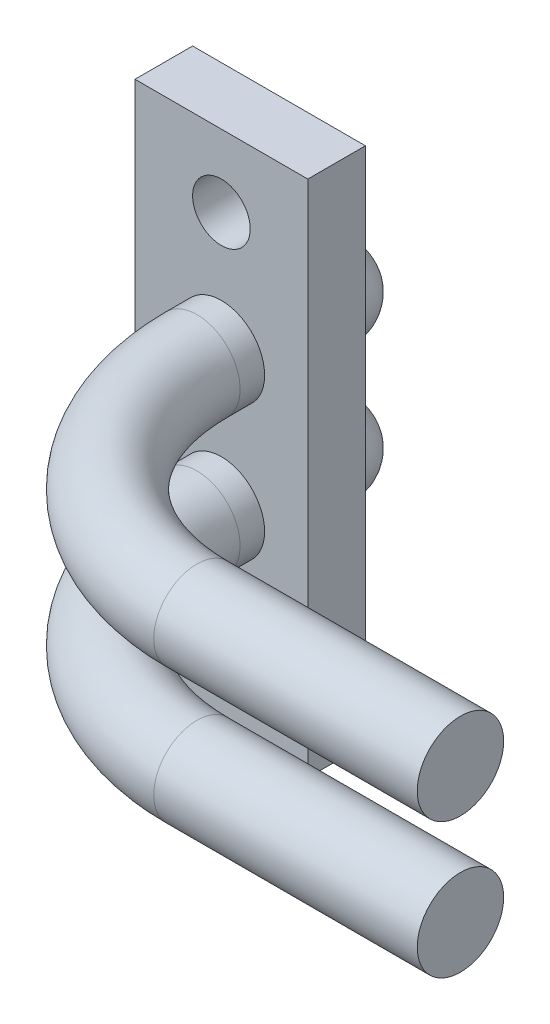
SolidWorks part; units mm, degrees
ref_plane "Front Plane" through (0, 0, 0) normal (0, 0, 1) x (1, 0, 0)
ref_plane "Top Plane" through (0, 0, 0) normal (0, 1, 0) x (1, 0, 0)
ref_plane "Right Plane" through (0, 0, 0) normal (1, 0, 0) x (0, 0, -1)
sketch "Sketch1" plane through (0, 0, 0) normal (0, 0, 1) x (1, 0, 0)
  line L1 (-3, -9) -> (3, -9)
  line L2 (-3, -9) -> (-3, 9)
  line L3 (-3, 9) -> (3, 9)
  line L4 (3, -9) -> (3, 9)
  line L5 (-3, -9) -> (3, 9) construction
  line L6 (-3, 9) -> (3, -9) construction
  point P0 (0, 0)
  dimension "D1" = 18
  dimension "D2" = 6
extrude "Boss-Extrude1" add sketch "Sketch1" along normal blind 2
sketch "Sketch2" plane through (0, 0, 0) normal (0, 0, -1) x (-1, 0, 0)
  circle A0 centre (0, 2.35) radius 1.5
  circle A1 centre (0, -2.35) radius 1.5
  dimension "D2" = 3
  dimension "D1" = 4.7
  dimension "D3" = 2.35
extrude "Boss-Extrude2" add sketch "Sketch2" along normal blind 3
fillet "Fillet1" radius 1.5 2 edges at (-1.5, -2.35, -3) (-1.5, 2.35, -3)
sketch "Sketch3" plane through (0, 0, 2) normal (0, 0, 1) x (1, 0, 0)
  circle A0 centre (0, -2.35) radius 1.5 construction
  circle A1 centre (0, 2.35) radius 1.5 construction
  circle A2 centre (0, -2.35) radius 1.5
  circle A3 centre (0, 2.35) radius 1.5
ref_plane "Plane1" through (0, 2.35, 0) normal (0, 1, 0) x (-1, 0, 0)
sketch "Sketch4" plane through (0, 2.35, 0) normal (0, 1, 0) x (-1, 0, 0)
  line L0 (0, 2) -> (0, 2.85)
  line L1 (1.5, 2) -> (-1.5, 2) construction
  line L2 (-7.5, 10.35) -> (-16.65, 10.35)
  arc A0 (0, 2.85) -> (-7.5, 10.35) centre (-7.5, 2.85) ccw
  point P8 (0, 10.35)
  dimension "D3" = 7.5
  dimension "D1" = 16.65
  dimension "D2" = 8.35
sweep "Sweep1" add profiles "Sketch3" path "Sketch4"
sketch "Sketch5" plane through (0, 0, 2) normal (0, 0, 1) x (1, 0, 0)
  line L0 (0, 0) -> (0, 6.5) construction
  line L1 (0, 0) -> (3, 0) construction
  line L2 (3, -9) -> (3, 9) construction
  line L3 (3, 9) -> (-3, 9) construction
  circle A0 centre (0, 6.5) radius 1
  circle A1 centre (0, -6.5) radius 1
  dimension "D1" = 2
  dimension "D2" = 2.5
extrude "Cut-Extrude1" cut sketch "Sketch5" against normal through all
